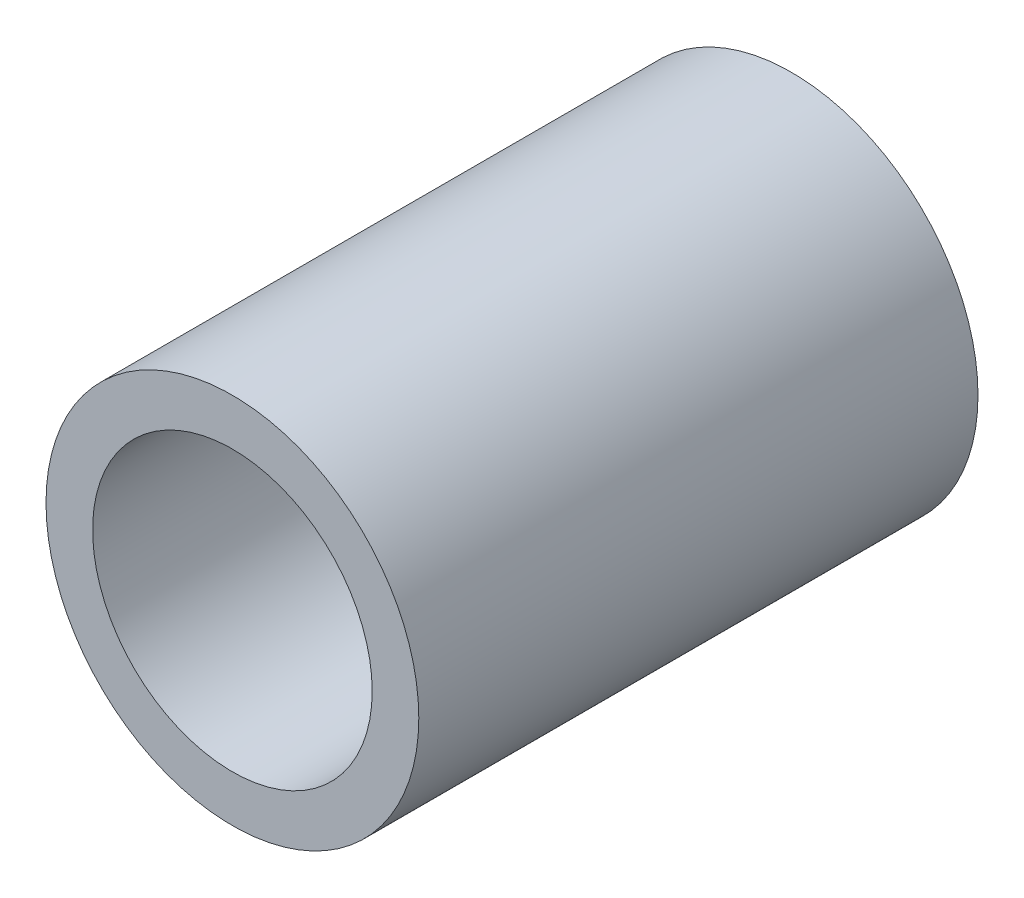
SolidWorks part; units mm, degrees
ref_plane "Plan de face" through (0, 0, 0) normal (0, 0, 1) x (1, 0, 0)
ref_plane "Plan de dessus" through (0, 0, 0) normal (0, 1, 0) x (1, 0, 0)
ref_plane "Plan de droite" through (0, 0, 0) normal (1, 0, 0) x (0, 0, -1)
sketch "Esquisse1" plane through (0, 0, 0) normal (0, 0, 1) x (1, 0, 0)
  circle A0 centre (0, 0) radius 40
  circle A1 centre (0, 0) radius 30
  dimension "D1" = 80
  dimension "D2" = 60
extrude "Boss.-Extru.1" add sketch "Esquisse1" along normal blind 120
